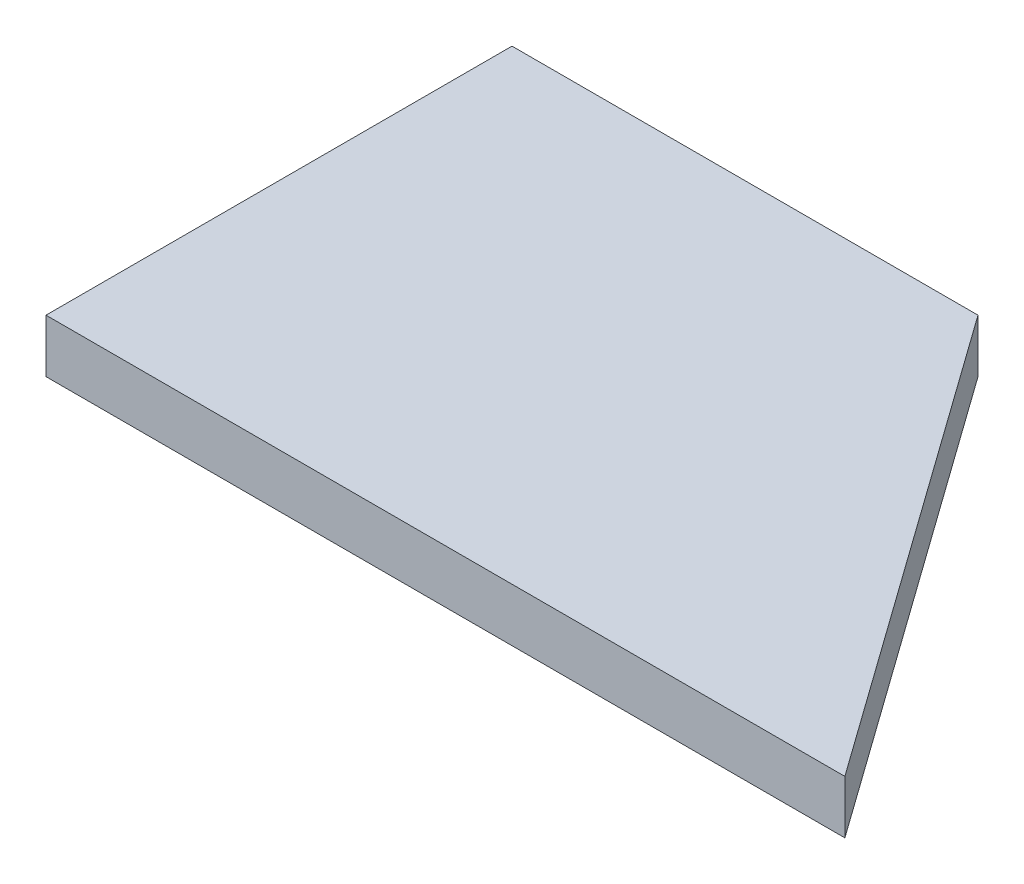
SolidWorks part; units mm, degrees
material "ASTM A36 Steel"
ref_plane "Front Plane" through (0, 0, 0) normal (0, 0, 1) x (1, 0, 0)
ref_plane "Top Plane" through (0, 0, 0) normal (0, 1, 0) x (1, 0, 0)
ref_plane "Right Plane" through (0, 0, 0) normal (1, 0, 0) x (0, 0, -1)
sketch "Sketch1" plane through (0, 0, 0) normal (0, 1, 0) x (1, 0, 0)
  line L0 (0, 0) -> (120, 0)
  line L1 (0, 0) -> (0, 70)
  line L2 (0, 70) -> (70, 70)
  line L3 (70, 70) -> (120, 0)
extrude "Boss-Extrude1" add sketch "Sketch1" along normal blind 8
